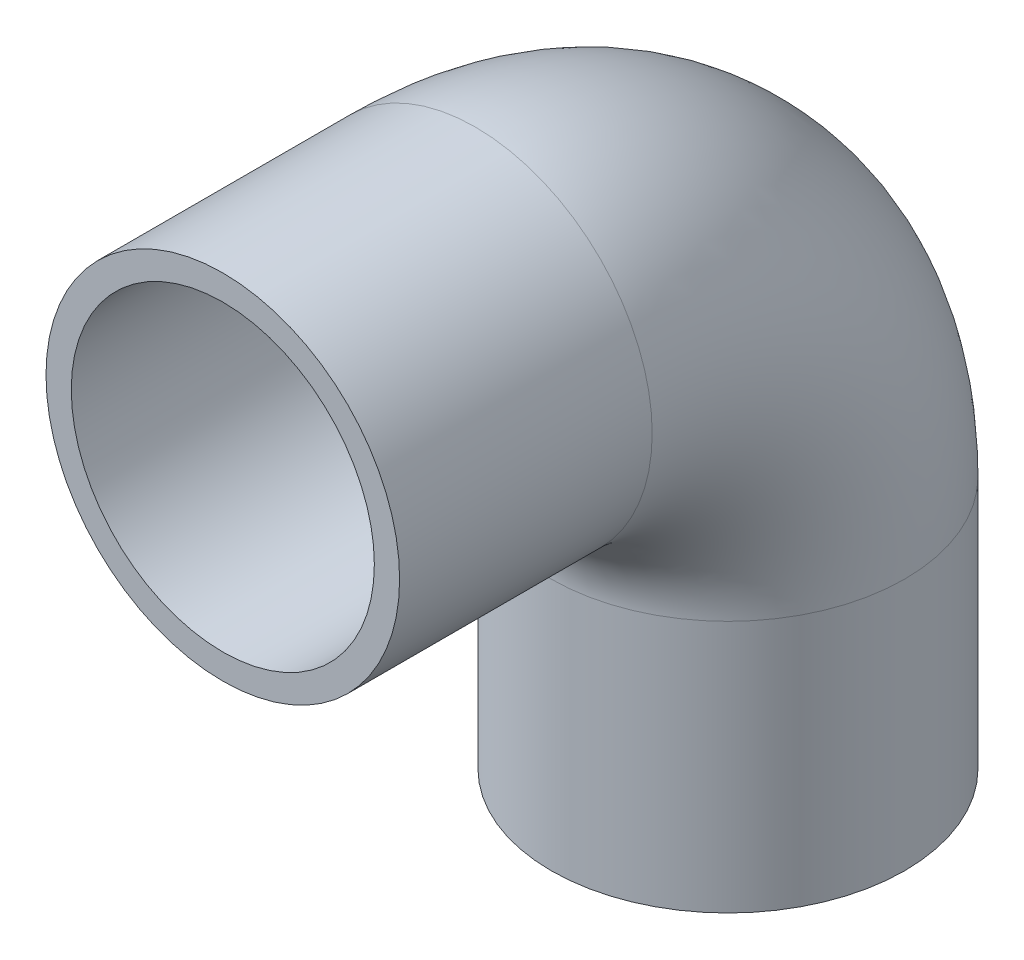
SolidWorks part; units mm, degrees
ref_plane "前视基准面" through (0, 0, 0) normal (0, 0, 1) x (1, 0, 0)
ref_plane "上视基准面" through (0, 0, 0) normal (0, 1, 0) x (1, 0, 0)
ref_plane "右视基准面" through (0, 0, 0) normal (1, 0, 0) x (0, 0, -1)
sketch "草图1" plane through (0, 0, 0) normal (0, 0, 1) x (1, 0, 0)
  circle A0 centre (0, 0) radius 7
  dimension "D1" = 14
sketch "草图2" plane through (0, 0, 0) normal (1, 0, 0) x (0, 0, -1)
  line L0 (0, 0) -> (10, 0)
  line L1 (20, -10) -> (20, -20)
  arc A0 (20, -10) -> (10, 0) centre (10, -10) ccw
  point P6 (20, 0)
  dimension "D2" = 10
  dimension "D1" = 20
sweep "扫描1" add profiles "草图1" path "草图2"
sketch "草图3" plane through (0, 0, 0) normal (0, 0, 1) x (1, 0, 0)
  circle A0 centre (0, 0) radius 6
  dimension "D1" = 12
sketch "草图4" plane through (0, 0, 0) normal (1, 0, 0) x (0, 0, -1)
  line L0 (0, 0) -> (10, 0)
  line L1 (20, -10) -> (20, -20)
  arc A0 (20, -10) -> (10, 0) centre (10, -10) ccw
  point P6 (20, 0)
  dimension "D2" = 10
  dimension "D1" = 20
sweep "切除-扫描1" cut profiles "草图3" path "草图4"
